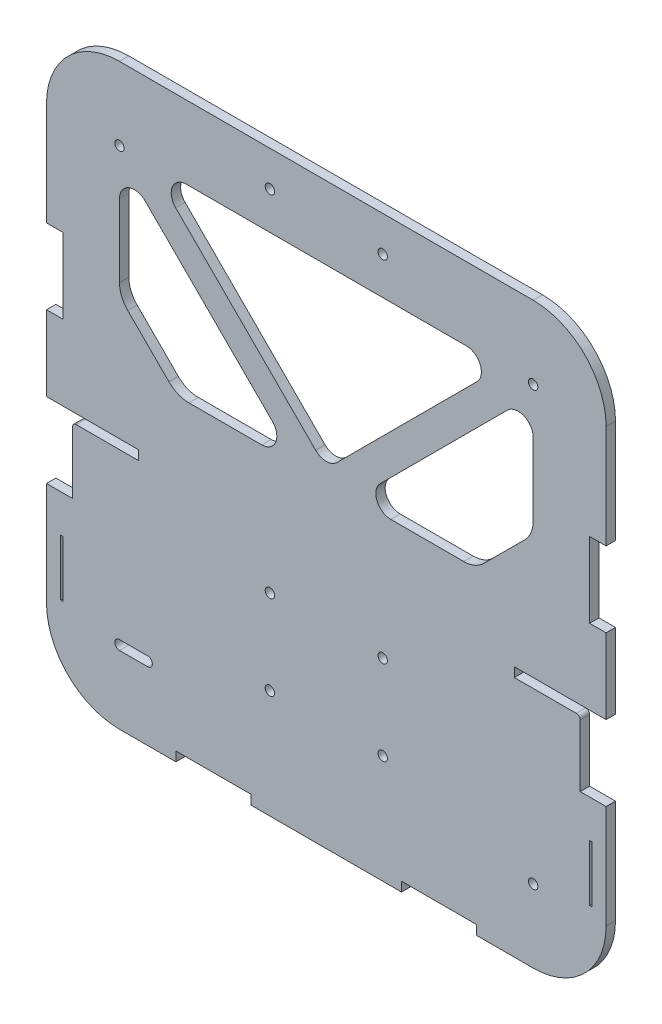
SolidWorks part; units mm, degrees
material "Maple"
ref_plane "Front Plane" through (0, 0, 0) normal (0, 0, 1) x (1, 0, 0)
ref_plane "Top Plane" through (0, 0, 0) normal (0, 1, 0) x (1, 0, 0)
ref_plane "Right Plane" through (0, 0, 0) normal (1, 0, 0) x (0, 0, -1)
ref_plane "Plane1" through (0, 0, -196.85) normal (0, 0, 1) x (1, 0, 0)
sketch "Sketch1" plane through (0, 0, -196.85) normal (0, 0, 1) x (1, 0, 0)
  line L0 (46.4188, -88.9) -> (21.7892, -88.9)
  line L1 (18.1971, -80.2279) -> (61.1779, -37.2471)
  line L2 (69.85, -40.8392) -> (69.85, -65.4688)
  line L3 (-3.5921, -81.3625) -> (-50.8825, -34.0721)
  line L4 (-47.2904, -25.4) -> (47.2904, -25.4)
  line L5 (50.8825, -34.0721) -> (3.5921, -81.3625)
  line L6 (-94.488, -136.525) -> (-94.488, -171.45)
  line L7 (-69.85, -196.088) -> (69.85, -196.088)
  line L8 (94.488, -171.45) -> (94.488, -136.525)
  line L9 (94.488, -136.525) -> (85.725, -136.525)
  line L10 (85.725, -136.525) -> (85.725, -115.57)
  line L11 (84.455, -114.3) -> (63.5, -114.3)
  line L12 (63.5, -114.3) -> (63.5, -111.125)
  line L13 (63.5, -111.125) -> (94.488, -111.125)
  line L14 (94.488, -111.125) -> (94.488, -85.725)
  line L15 (94.488, -85.725) -> (88.9, -85.725)
  line L16 (88.9, -85.725) -> (88.9, -60.325)
  line L17 (88.9, -60.325) -> (94.488, -60.325)
  line L18 (94.488, -60.325) -> (94.488, -25.4)
  line L19 (69.85, -0.762) -> (-69.85, -0.762)
  line L20 (-94.488, -25.4) -> (-94.488, -60.325)
  line L21 (-94.488, -60.325) -> (-88.9, -60.325)
  line L22 (-88.9, -60.325) -> (-88.9, -85.725)
  line L23 (-88.9, -85.725) -> (-94.488, -85.725)
  line L24 (-94.488, -85.725) -> (-94.488, -111.125)
  line L25 (-94.488, -111.125) -> (-63.5, -111.125)
  line L26 (-63.5, -111.125) -> (-63.5, -114.3)
  line L27 (-63.5, -114.3) -> (-84.455, -114.3)
  line L28 (-85.725, -115.57) -> (-85.725, -136.525)
  line L29 (-85.725, -136.525) -> (-94.488, -136.525)
  line L30 (-69.85, -65.4688) -> (-69.85, -40.8392)
  line L31 (-61.1779, -37.2471) -> (-18.1971, -80.2279)
  line L32 (-21.7892, -88.9) -> (-46.4188, -88.9)
  line L33 (0, 0) -> (0, -50000) construction
  line L34 (-67.0602, -72.204) -> (-53.154, -86.1102)
  line L35 (-19.05, -130.831) -> (19.05, -130.831) construction
  line L36 (-19.05, -130.831) -> (-19.05, -159.406) construction
  line L37 (-19.05, -159.406) -> (19.05, -159.406) construction
  line L38 (19.05, -130.831) -> (19.05, -159.406) construction
  line L39 (-61.1779, -139.7) -> (73.825, -139.7) construction
  line L40 (-61.1779, -139.7) -> (-61.1779, -25.8853) construction
  line L41 (-61.1779, -25.8853) -> (73.825, -25.8853) construction
  line L42 (73.825, -139.7) -> (73.825, -25.8853) construction
  line L43 (67.0602, -72.204) -> (53.154, -86.1102)
  line L44 (88.9, -149.225) -> (88.9, -168.275)
  line L45 (-89.6937, -149.225) -> (-88.9, -149.225)
  line L46 (-89.6937, -149.225) -> (-89.6937, -168.275)
  line L47 (-89.6937, -168.275) -> (-88.9, -168.275)
  line L48 (-88.9, -149.225) -> (-88.9, -168.275)
  line L49 (89.6937, -168.275) -> (88.9, -168.275)
  line L50 (89.6938, -149.225) -> (89.6937, -168.275)
  line L51 (89.6938, -149.225) -> (88.9, -149.225)
  line L52 (-50.8, -196.088) -> (-50.8, -192.913)
  line L53 (-50.8, -192.913) -> (-25.4, -192.913)
  line L54 (-25.4, -192.913) -> (-25.4, -196.088)
  line L55 (-69.85, -169.8625) -> (-60.325, -169.8625)
  line L56 (-69.85, -173.0375) -> (-60.325, -173.0375)
  line L57 (50.8, -196.088) -> (50.8, -192.913)
  line L58 (25.4, -192.913) -> (25.4, -196.088)
  line L59 (50.8, -192.913) -> (25.4, -192.913)
  circle A0 centre (-19.05, -12.7) radius 1.5875
  circle A1 centre (19.05, -12.7) radius 1.5875
  circle A2 centre (-69.85, -25.4) radius 1.5875
  circle A3 centre (69.85, -25.4) radius 1.5875
  circle A4 centre (-69.85, -171.45) radius 1.5875
  circle A5 centre (69.85, -171.45) radius 1.5875
  arc A6 (69.85, -65.4688) -> (67.0602, -72.204) centre (60.325, -65.4688) cw
  arc A7 (21.7892, -88.9) -> (18.1971, -80.2279) centre (21.7892, -83.82) cw
  arc A8 (61.1779, -37.2471) -> (69.85, -40.8392) centre (64.77, -40.8392) cw
  circle A9 centre (-83.82, -84.8367) radius 1.5875
  arc A10 (3.5921, -81.3625) -> (-3.5921, -81.3625) centre (0, -77.7704) cw
  arc A11 (-50.8825, -34.0721) -> (-47.2904, -25.4) centre (-47.2904, -30.48) cw
  arc A12 (47.2904, -25.4) -> (50.8825, -34.0721) centre (47.2904, -30.48) cw
  arc A13 (-94.488, -171.45) -> (-69.85, -196.088) centre (-69.85, -171.45) ccw
  arc A14 (69.85, -196.088) -> (94.488, -171.45) centre (69.85, -171.45) ccw
  arc A15 (94.488, -25.4) -> (69.85, -0.762) centre (69.85, -25.4) ccw
  arc A16 (-69.85, -0.762) -> (-94.488, -25.4) centre (-69.85, -25.4) ccw
  arc A17 (-69.85, -40.8392) -> (-61.1779, -37.2471) centre (-64.77, -40.8392) cw
  arc A18 (-18.1971, -80.2279) -> (-21.7892, -88.9) centre (-21.7892, -83.82) cw
  arc A19 (46.4188, -88.9) -> (53.154, -86.1102) centre (46.4188, -79.375) ccw
  arc A20 (85.725, -115.57) -> (84.455, -114.3) centre (84.455, -115.57) ccw
  arc A21 (-84.455, -114.3) -> (-85.725, -115.57) centre (-84.455, -115.57) ccw
  circle A22 centre (-19.05, -130.831) radius 1.5875
  circle A23 centre (19.05, -130.831) radius 1.5875
  circle A24 centre (19.05, -159.406) radius 1.5875
  circle A25 centre (-19.05, -159.406) radius 1.5875
  arc A26 (-46.4188, -88.9) -> (-53.154, -86.1102) centre (-46.4188, -79.375) cw
  arc A27 (-69.85, -65.4688) -> (-67.0602, -72.204) centre (-60.325, -65.4688) ccw
  circle A28 centre (-60.325, -171.45) radius 1.5875
  point P84 (0, -130.831)
  point P95 (-69.85, -69.4142)
  dimension "D1" = 1.27
  dimension "D4" = 3.175
  dimension "D7" = 3.175
  dimension "D11" = 9.525
  dimension "D2" = 38.1
  dimension "D3" = 28.575
  dimension "D5" = 56.388
  dimension "D6" = 19.706
  dimension "D8" = 9.525
  dimension "D9" = 9.525
  dimension "D10" = 28.575
  dimension "D12" = 0.7937
  dimension "D13" = 19.05
  dimension "D14" = 12.7
  dimension "D15" = 3.175
  dimension "D16" = 3.175
  dimension "D17" = 25.4
  dimension "D18" = 25.4
  dimension "D19" = 9.525
extrude "Boss-Extrude1" add sketch "Sketch1" against normal blind 3.175 contours L27 A21 L28 L29 L6 A13 L7 L52 L53 L54 L58 L59 L57 A14 L8 L9 L10 A20 L11 L12 L13 L14 L15 L16 L17 L18 A15 L19 A16 L20 L21 L22 L23 L24 L25 L26 A28 L56 A4 L55 A27 L30 A17 L31 A18 L32 A26 | A9
